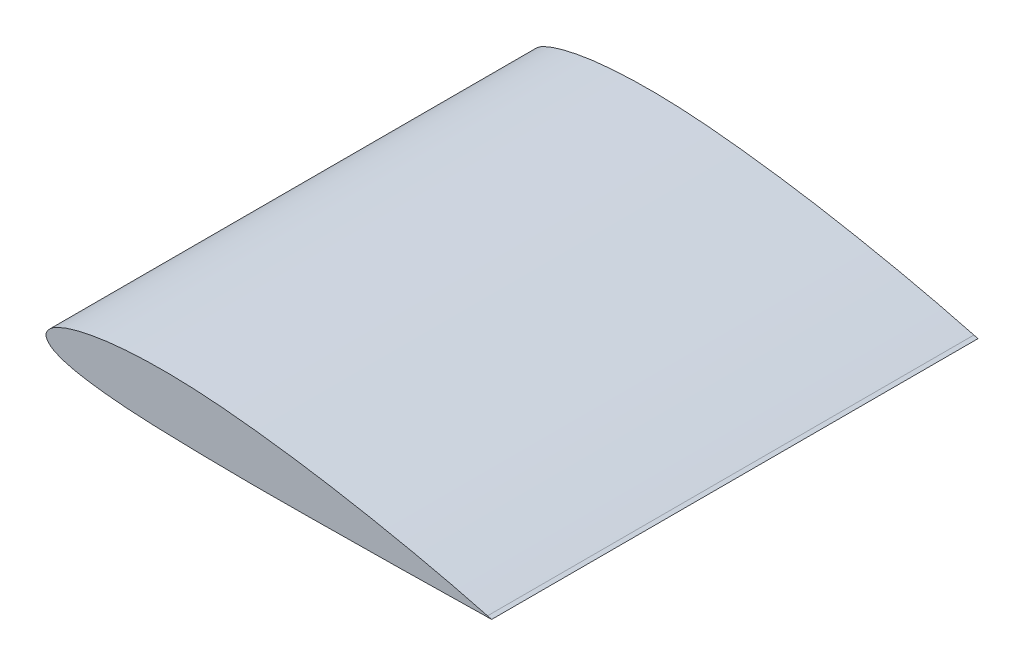
SolidWorks part; units mm, degrees
ref_plane "Front Plane" through (0, 0, 0) normal (0, 0, 1) x (1, 0, 0)
ref_plane "Top Plane" through (0, 0, 0) normal (0, 1, 0) x (1, 0, 0)
ref_plane "Right Plane" through (0, 0, 0) normal (1, 0, 0) x (0, 0, -1)
curve "Curve2"
  spline degree 3 poles (304.8, 0.3962, 0) (299.7228, 1.4366, 0) (289.5818, 3.5147, 0) (269.2823, 7.3209, 0) (243.8943, 11.5382, 0) (213.4085, 15.9029, 0) (182.9278, 19.543, 0) (152.4338, 22.2083, 0) (121.9468, 24.0133, 0) (96.5105, 24.3188, 0) (76.1816, 23.4772, 0) (60.9224, 22.244, 0) (45.6439, 20.2912, 0) (32.9285, 17.8864, 0) (22.7915, 15.1658, 0) (15.1062, 12.6924, 0) (8.5948, 9.8104, 0) (2.9782, 6.3164, 0) (-1.9197, 0.2739, 0) (3.1679, -5.0372, 0) (8.6795, -7.4596, 0) (15.1622, -9.2997, 0) (22.8222, -10.619, 0) (32.9998, -11.7449, 0) (45.7039, -12.6115, 0) (60.9582, -12.959, 0) (76.2017, -12.9105, 0) (96.5236, -12.462, 0) (121.9283, -11.6548, 0) (152.4102, -10.25, 0) (182.8832, -8.4242, 0) (213.3615, -6.5264, 0) (243.8449, -4.6055, 0) (269.2394, -2.8363, 0) (289.5613, -1.4716, 0) (299.7202, -0.7547, 0) (304.8, -0.3962, 0) knots 0 0 0 0 0.025012 0.049959 0.099673 0.149206 0.198581 0.247805 0.296917 0.345953 0.370492 0.395091 0.419815 0.444799 0.45749 0.470406 0.483879 0.491264 0.503459 0.513609 0.520451 0.533235 0.545691 0.558032 0.582609 0.607135 0.631652 0.656174 0.705234 0.75432 0.803437 0.852566 0.901701 0.950849 0.975423 1 1 1 1
sketch "Sketch3" plane through (0, 0, 0) normal (0, 0, 1) x (1, 0, 0)
  line L1 (304.4028, -9.2063) -> (304.3618, -9.9977) construction
  line L2 (304.3823, -9.602) -> (0, 6.35) construction
  line L3 (0, 6.35) -> (0, 64.0858) construction
  line L4 (170.0406, 0) -> (-170.0406, 0) construction
  line L5 (0, -42.3746) -> (0, 42.3746) construction
  line L6 (0, 6.35) -> (76.0956, 2.362) construction
  line L7 (76.0956, 2.362) -> (77.3112, 25.5581) construction
  line L8 (76.0956, 2.362) -> (75.4146, -10.6316) construction
  line L9 (304.4028, -9.2063) -> (307.245, -9.9436)
  line L10 (307.245, -9.9436) -> (304.3618, -9.9977)
  spline S1 degree 3 poles (304.4028, -9.2063) (299.3864, -7.905) (289.3668, -5.3057) (269.2922, -0.4557) (244.1574, 5.0678) (213.9395, 11.0021) (183.6892, 16.2124) (153.3753, 20.45) (123.0239, 23.828) (97.6387, 25.4477) (77.2945, 25.6579) (61.9928, 25.215) (46.6346, 24.0545) (33.8125, 22.3102) (23.549, 20.1173) (15.7465, 18.0444) (9.0953, 15.503) (3.3058, 12.3041) (-1.8975, 6.5232) (2.9085, 0.9564) (8.2873, -1.7474) (14.6659, -3.92) (22.247, -5.6333) (32.3523, -7.2837) (44.994, -8.8056) (60.2092, -9.9409) (75.434, -10.6804) (95.7509, -11.2827) (121.1621, -11.7896) (151.6742, -11.9621) (182.1994, -11.7137) (212.7334, -11.3937) (243.2738, -11.0508) (268.7245, -10.5965) (289.0887, -10.284) (299.2705, -10.0931) (304.3618, -9.9977) knots 0 0 0 0 0.025012 0.049959 0.099673 0.149206 0.198581 0.247805 0.296917 0.345953 0.370492 0.395091 0.419815 0.444799 0.45749 0.470406 0.483879 0.491264 0.503459 0.513609 0.520451 0.533235 0.545691 0.558032 0.582609 0.607135 0.631652 0.656174 0.705234 0.75432 0.803437 0.852566 0.901701 0.950849 0.975423 1 1 1 1
  dimension "D1" = 304.8
  dimension "D2" = 3
  dimension "D3" = 6.35
  dimension "D4" = 76.2
  dimension "D5" = 36.2393
ref_plane "Plane2" through (0, 0, 335.28) normal (0, 0, 1) x (1, 0, 0)
sketch "Sketch4" plane through (0, 0, 335.28) normal (0, 0, 1) x (1, 0, 0)
  line L0 (304.4028, -9.2063) -> (304.3618, -9.9977) construction
  line L1 (304.3823, -9.602) -> (0, 6.35) construction
  line L2 (0, 6.35) -> (0, 8.7544) construction
  line L3 (0, 6.35) -> (0, 64.0858) construction
  line L4 (170.0406, 0) -> (-170.0406, 0) construction
  line L5 (304.3618, -9.9977) -> (307.245, -9.9436)
  line L6 (307.245, -9.9436) -> (304.4028, -9.2063)
  spline S0 degree 3 poles (304.4028, -9.2063) (299.3864, -7.905) (289.3668, -5.3057) (269.2922, -0.4557) (244.1574, 5.0678) (213.9395, 11.0021) (183.6892, 16.2124) (153.3753, 20.45) (123.0239, 23.828) (97.6387, 25.4477) (77.2945, 25.6579) (61.9928, 25.215) (46.6346, 24.0545) (33.8125, 22.3102) (23.549, 20.1173) (15.7465, 18.0444) (9.0953, 15.503) (3.3058, 12.3041) (-1.8975, 6.5232) (2.9085, 0.9564) (8.2873, -1.7474) (14.6659, -3.92) (22.247, -5.6333) (32.3523, -7.2837) (44.994, -8.8056) (60.2092, -9.9409) (75.434, -10.6804) (95.7509, -11.2827) (121.1621, -11.7896) (151.6742, -11.9621) (182.1994, -11.7137) (212.7334, -11.3937) (243.2738, -11.0508) (268.7245, -10.5965) (289.0887, -10.284) (299.2705, -10.0931) (304.3618, -9.9977) knots 0 0 0 0 0.025012 0.049959 0.099673 0.149206 0.198581 0.247805 0.296917 0.345953 0.370492 0.395091 0.419815 0.444799 0.45749 0.470406 0.483879 0.491264 0.503459 0.513609 0.520451 0.533235 0.545691 0.558032 0.582609 0.607135 0.631652 0.656174 0.705234 0.75432 0.803437 0.852566 0.901701 0.950849 0.975423 1 1 1 1
  dimension "D1" = 304.8
  dimension "D2" = 3
loft "Loft1" add profiles "Sketch3", "Sketch4"
